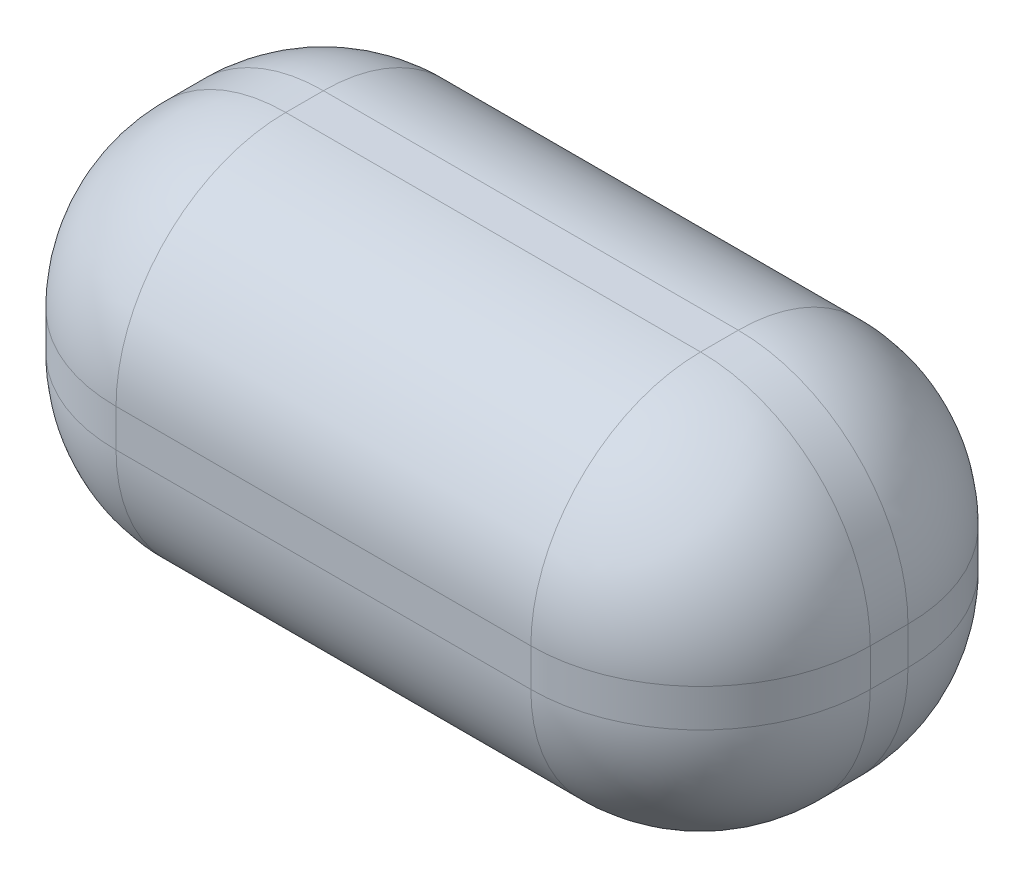
SolidWorks part; units mm, degrees
ref_plane "Front Plane" through (0, 0, 0) normal (0, 0, 1) x (1, 0, 0)
ref_plane "Top Plane" through (0, 0, 0) normal (0, 1, 0) x (1, 0, 0)
ref_plane "Right Plane" through (0, 0, 0) normal (1, 0, 0) x (0, 0, -1)
sketch "Sketch1" plane through (0, 0, 0) normal (0, 0, 1) x (1, 0, 0)
  line L1 (-100, -50) -> (100, -50)
  line L2 (-100, -50) -> (-100, 50)
  line L3 (-100, 50) -> (100, 50)
  line L4 (100, -50) -> (100, 50)
  line L5 (-100, -50) -> (100, 50) construction
  line L6 (-100, 50) -> (100, -50) construction
  point P0 (0, 0)
  dimension "D1" = 200
  dimension "D2" = 100
extrude "Boss-Extrude1" add sketch "Sketch1" along normal mid plane 100
fillet "Fillet1" radius 45 12 edges at (-100, -50, 0) (-100, 0, -50) (0, -50, -50) (100, -50, 0) (100, 0, -50) (0, -50, 50) (-100, 0, 50) (100, 0, 50) (100, 50, 0) (0, 50, 50) (-100, 50, 0) (0, 50, -50)
